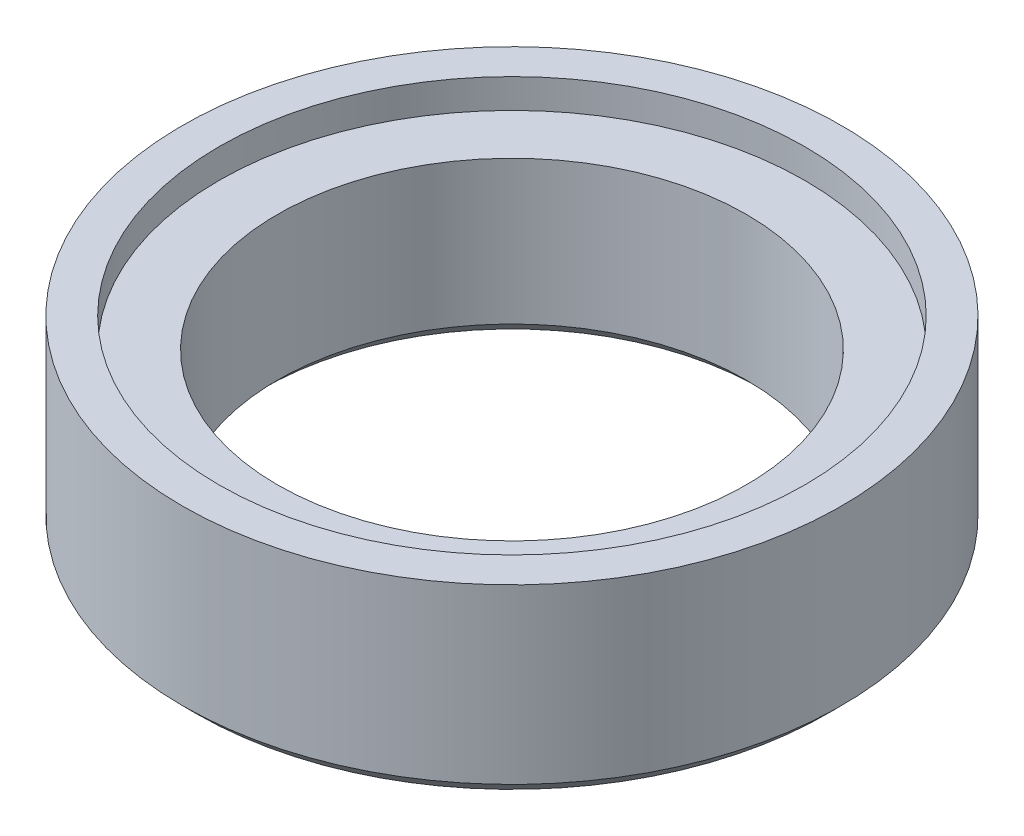
SolidWorks part; units mm, degrees
ref_plane "Front Plane" through (0, 0, 0) normal (0, 0, 1) x (1, 0, 0)
ref_plane "Top Plane" through (0, 0, 0) normal (0, 1, 0) x (1, 0, 0)
ref_plane "Right Plane" through (0, 0, 0) normal (1, 0, 0) x (0, 0, -1)
sketch "Sketch1" plane through (0, 0, 0) normal (0, 1, 0) x (1, 0, 0)
  circle A0 centre (0, 0) radius 11.25
  circle A1 centre (0, 0) radius 8
  dimension "D1" = 16
  dimension "D2" = 22.5
extrude "Boss-Extrude1" add sketch "Sketch1" along normal blind 6.4
sketch "Sketch2" plane through (0, 6.4, 0) normal (0, 1, 0) x (1, 0, 0)
  circle A0 centre (0, 0) radius 10
  dimension "D1" = 20
extrude "Cut-Extrude1" cut sketch "Sketch2" against normal blind 1
chamfer "Chamfer1" distance 0.5 angle 45 2 edges at (0, 0, 8) (0, 0, 11.25)
